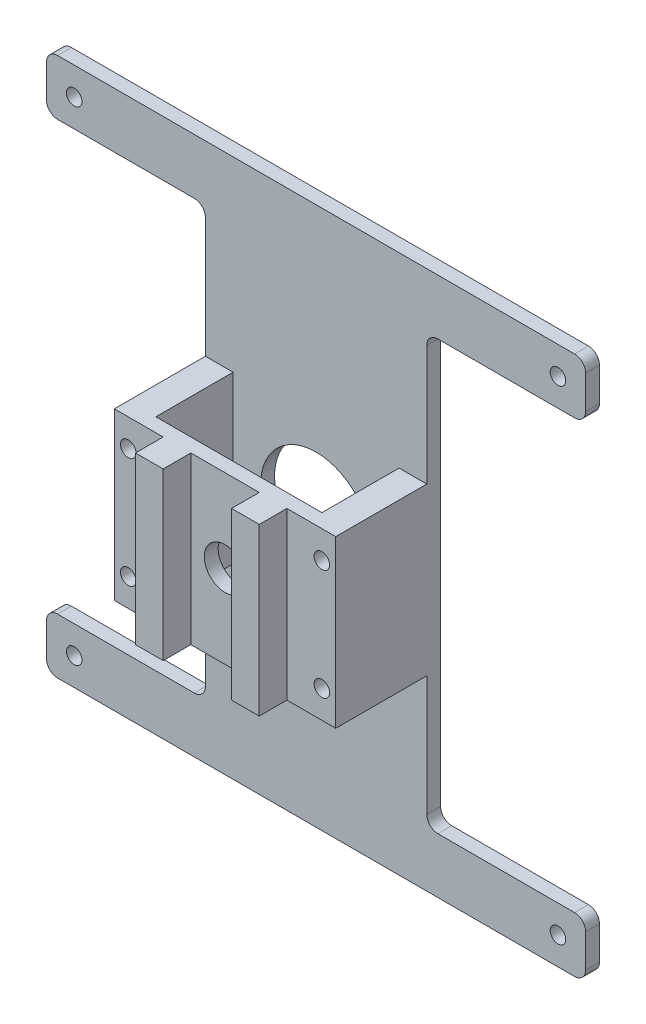
SolidWorks part; units mm, degrees
ref_plane "Front Plane" through (0, 0, 0) normal (0, 0, 1) x (1, 0, 0)
ref_plane "Top Plane" through (0, 0, 0) normal (0, 1, 0) x (1, 0, 0)
ref_plane "Right Plane" through (0, 0, 0) normal (1, 0, 0) x (0, 0, -1)
sketch "Sketch1" plane through (0, 0, 0) normal (0, 0, 1) x (1, 0, 0)
  line L0 (0, -78.5) -> (0, 78.5) construction
  line L5 (0, -78.5) -> (0, -76.7141) construction
  line L6 (0, 0) -> (-55.5079, 55.5079) construction
  line L7 (0, -12.7) -> (0, 0) construction
  line L8 (0, 0) -> (55.5079, 55.5079) construction
  line L9 (25.4, 49.1579) -> (61.8579, 49.1579)
  line L11 (-25.4, -19.05) -> (-25.4, 49.1579)
  line L12 (-19.05, 61.8579) -> (19.05, 61.8579)
  line L13 (25.4, -19.05) -> (25.4, 49.1579)
  line L14 (-61.8579, 49.1579) -> (-25.4, 49.1579)
  line L15 (-61.8579, 49.1579) -> (-61.8579, 61.8579)
  line L16 (-61.8579, 61.8579) -> (61.8579, 61.8579)
  line L17 (61.8579, 49.1579) -> (61.8579, 61.8579)
  line L18 (0, 0) -> (-90.173, 0) construction
  line L19 (0, 0) -> (55.5079, -55.5079) construction
  line L20 (0, 0) -> (-8.9803, -8.9803) construction
  line L21 (61.8579, -49.1579) -> (61.8579, -61.8579)
  line L22 (-61.8579, -61.8579) -> (61.8579, -61.8579)
  line L23 (-61.8579, -49.1579) -> (-61.8579, -61.8579)
  line L24 (-61.8579, -49.1579) -> (-25.4, -49.1579)
  line L25 (-19.05, -61.8579) -> (19.05, -61.8579)
  line L26 (25.4, -49.1579) -> (61.8579, -49.1579)
  line L27 (-25.4, -49.1579) -> (-25.4, -19.05)
  line L28 (25.4, -49.1579) -> (25.4, -19.05)
  circle A2 centre (0, 0) radius 12.7
  circle A3 centre (-55.5079, 55.5079) radius 1.7859
  circle A5 centre (55.5079, 55.5079) radius 1.7859
  circle A6 centre (55.5079, -55.5079) radius 1.7859
  circle A7 centre (-55.5079, -55.5079) radius 1.7859
  point P37 (-25.4, -19.05)
  dimension "D1" = 45
  dimension "D3" = 25.4
  dimension "D4" = 3.5719
  dimension "D2" = 50.8
  dimension "D5" = 78.5
  dimension "D6" = 25.4
  dimension "D7" = 45
  dimension "D8" = 25.4
  dimension "D9" = 6.35
  dimension "D10" = 12.7
  dimension "D11" = 6.35
  dimension "D12" = 6.35
extrude "Boss-Extrude1" add sketch "Sketch1" along normal blind 3.175
sketch "Sketch2" plane through (0, 0, 3.175) normal (0, 0, 1) x (1, 0, 0)
  line L1 (19.05, -19.05) -> (25.4, -19.05)
  line L2 (19.05, -19.05) -> (19.05, 19.05)
  line L3 (19.05, 19.05) -> (25.4, 19.05)
  line L4 (25.4, -19.05) -> (25.4, 19.05)
  line L5 (-25.4, -19.05) -> (-19.05, -19.05)
  line L6 (-25.4, -19.05) -> (-25.4, 19.05)
  line L7 (-25.4, 19.05) -> (-19.05, 19.05)
  line L8 (-19.05, -19.05) -> (-19.05, 19.05)
  line L9 (-25.4, -49.1579) -> (-25.4, 49.1579) construction
  line L10 (25.4, -49.1579) -> (25.4, 49.1579) construction
  line L11 (19.05, 0) -> (0, 0) construction
  line L12 (0, 0) -> (-19.05, 0) construction
  dimension "D1" = 6.35
  dimension "D2" = 38.1
extrude "Boss-Extrude2" add sketch "Sketch2" along normal blind 17.7165 contours L4 L3 L2 L1
sketch "Sketch3" plane through (0, 0, 20.8915) normal (0, 0, 1) x (1, 0, 0)
  line L0 (-25.4, 19.05) -> (-25.4, -19.05) construction
  line L1 (-25.4, -19.05) -> (25.4, -19.05)
  line L2 (-25.4, -19.05) -> (-25.4, 19.05)
  line L3 (-25.4, 19.05) -> (25.4, 19.05)
  line L4 (25.4, -19.05) -> (25.4, 19.05)
  line L5 (-25.4, -19.05) -> (-19.05, -19.05) construction
  circle A0 centre (0, 0) radius 4.7625
  point P9 (0, 0)
  dimension "D1" = 9.525
extrude "Boss-Extrude3" add sketch "Sketch3" along normal blind 3.175
sketch "Sketch4" plane through (0, 0, 24.0665) normal (0, 0, 1) x (1, 0, 0)
  line L0 (-25.4, -19.05) -> (25.4, -19.05) construction
  line L1 (14.1986, -19.05) -> (7.8486, -19.05)
  line L2 (14.1986, -19.05) -> (14.1986, 19.05)
  line L3 (14.1986, 19.05) -> (7.8486, 19.05)
  line L4 (7.8486, -19.05) -> (7.8486, 19.05)
  line L5 (25.4, 19.05) -> (-25.4, 19.05) construction
  line L6 (7.8486, 0) -> (0, 0) construction
  line L7 (-7.8486, -19.05) -> (-14.1986, -19.05)
  line L8 (-7.8486, -19.05) -> (-7.8486, 19.05)
  line L9 (-7.8486, 19.05) -> (-14.1986, 19.05)
  line L10 (-14.1986, -19.05) -> (-14.1986, 19.05)
  line L11 (0, 0) -> (-7.8486, 0) construction
  dimension "D1" = 6.35
  dimension "D2" = 15.6972
extrude "Boss-Extrude4" add sketch "Sketch4" along normal blind 6.35
fillet "Fillet1" radius 2.54 12 edges at (-25.4, 49.1579, 1.5875) (-61.8579, 49.1579, 1.5875) (-61.8579, 61.8579, 1.5875) (61.8579, 61.8579, 1.5875) (61.8579, 49.1579, 1.5875) (25.4, 49.1579, 1.5875) (25.4, -49.1579, 1.5875) (61.8579, -49.1579, 1.5875) (61.8579, -61.8579, 1.5875) (-25.4, -49.1579, 1.5875) (-61.8579, -49.1579, 1.5875) (-61.8579, -61.8579, 1.5875)
sketch "Sketch6" plane through (0, 0, 0) normal (0, 0, -1) x (-1, 0, 0)
  line L0 (-25.4, -46.6179) -> (-25.4, 46.6179) construction
  line L1 (-22.225, 12.7) -> (22.225, 12.7) construction
  line L2 (-22.225, 12.7) -> (-22.225, -12.7) construction
  line L3 (-22.225, -12.7) -> (22.225, -12.7) construction
  line L4 (22.225, 12.7) -> (22.225, -12.7) construction
  line L5 (-22.225, 12.7) -> (22.225, -12.7) construction
  line L6 (-22.225, -12.7) -> (22.225, 12.7) construction
  circle A0 centre (-22.225, -12.7) radius 1.7859
  circle A1 centre (-22.225, 12.7) radius 1.7859
  circle A2 centre (22.225, 12.7) radius 1.7859
  circle A3 centre (22.225, -12.7) radius 1.7859
  point P0 (0, 0)
  dimension "D3" = 3.5719
  dimension "D1" = 25.4
  dimension "D2" = 3.175
extrude "Cut-Extrude2" cut sketch "Sketch6" against normal up to next
